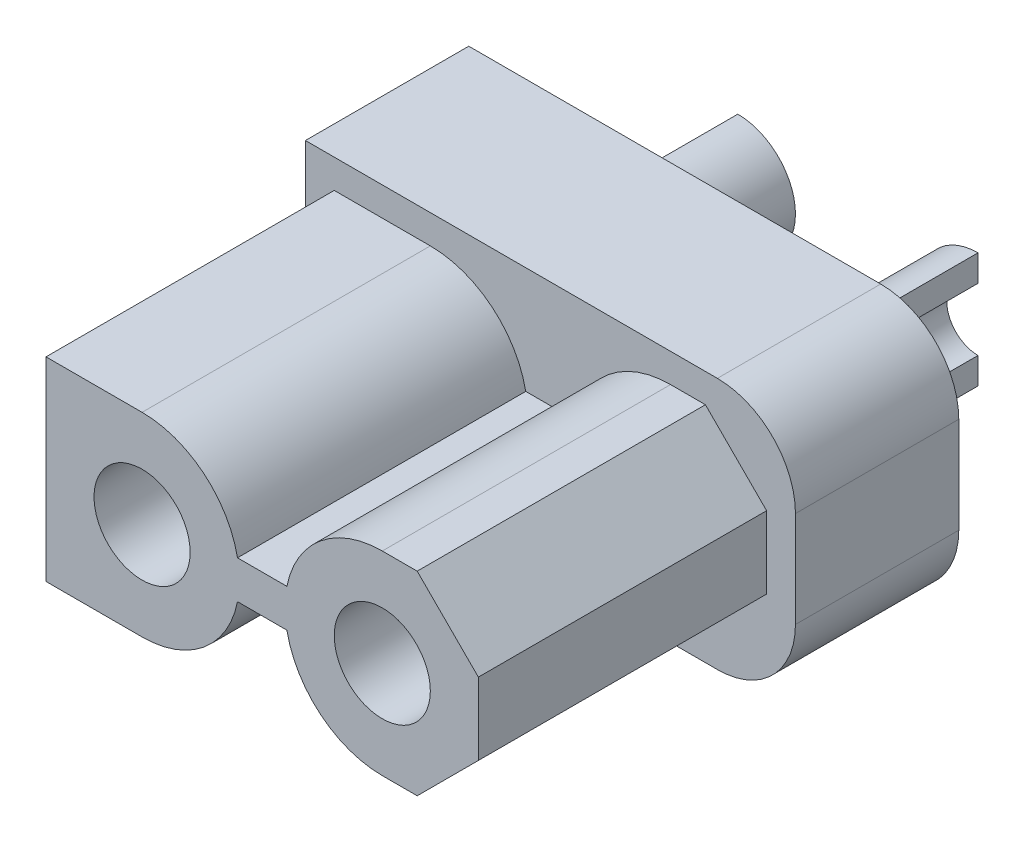
SolidWorks part; units mm, degrees
ref_plane "Front Plane" through (0, 0, 0) normal (0, 0, 1) x (1, 0, 0)
ref_plane "Top Plane" through (0, 0, 0) normal (0, 1, 0) x (1, 0, 0)
ref_plane "Right Plane" through (0, 0, 0) normal (1, 0, 0) x (0, 0, -1)
sketch "Sketch1" plane through (0, 0, 0) normal (0, 0, 1) x (1, 0, 0)
  line L0 (0, 0) -> (10.2, 0) construction
  line L1 (0, -2.625) -> (0, 2.625)
  line L2 (0, 2.625) -> (8.575, 2.625)
  line L4 (10.2, 1) -> (10.2, -1)
  line L5 (5.1, 0) -> (5.1, 1.3562) construction
  line L7 (0, -2.625) -> (8.575, -2.625)
  line L8 (0.5, 2.125) -> (8.3679, 2.125)
  line L9 (8.3679, 2.125) -> (9.7, 0.7929)
  line L10 (9.7, 0.7929) -> (9.7, -0.7929)
  line L11 (8.3679, -2.125) -> (9.7, -0.7929)
  line L12 (0.5, -2.125) -> (8.3679, -2.125)
  line L13 (0.5, -2.125) -> (0.5, 2.125)
  line L14 (8.575, 2.625) -> (10.2, 1) construction
  line L15 (8.575, -2.625) -> (10.2, -1) construction
  circle A0 centre (2.6, 0) radius 1
  circle A2 centre (7.6, 0) radius 1
  arc A3 (8.575, 2.625) -> (10.2, 1) centre (8.575, 1) cw
  arc A4 (8.575, -2.625) -> (10.2, -1) centre (8.575, -1) ccw
  dimension "D6" = 2
  dimension "D1" = 5.25
  dimension "D2" = 10.2
  dimension "D3" = 135
  dimension "D4" = 2.5
  dimension "D7" = 2
  dimension "D5" = 0.5
extrude "Boss-Extrude1" add sketch "Sketch1" along normal blind 3.4 contours L1 L7 A4 L4 A3 L2 L12 L13 L8 L9 L10 L11 | L13 L12 L11 L10 L9 L8 A0 A2 | A2 | A0
ref_plane "Plane1" through (0, 0, 1) normal (0, 0, -1) x (-1, 0, 0)
sketch "Sketch3" plane through (0, 0, 1) normal (0, 0, -1) x (-1, 0, 0)
  line L19 (-5.6139, 0.395) -> (-4.5861, 0.395)
  line L20 (-5.6139, 0.395) -> (-5.6139, -0.395)
  line L21 (-5.6139, -0.395) -> (-4.5861, -0.395)
  line L22 (-4.5861, 0.395) -> (-4.5861, -0.395)
  line L23 (-5.6139, 0.395) -> (-4.5861, -0.395) construction
  line L24 (-8.3265, -2.025) -> (-0.6, -2.025)
  line L25 (-0.6, -2.025) -> (-0.6, 2.025)
  line L26 (-0.6, 2.025) -> (-8.3265, 2.025)
  line L27 (-8.3265, 2.025) -> (-9.6, 0.7515)
  line L28 (-9.6, 0.7515) -> (-9.6, -0.7515)
  line L29 (-9.6, -0.7515) -> (-8.3265, -2.025)
  line L30 (-8.3265, -2.025) -> (-0.6, -2.025)
  line L31 (-0.6, -2.025) -> (-0.6, 2.025)
  line L32 (-0.6, 2.025) -> (-8.3265, 2.025)
  line L33 (-8.3265, 2.025) -> (-9.6, 0.7515)
  line L34 (-9.6, 0.7515) -> (-9.6, -0.7515)
  line L35 (-9.6, -0.7515) -> (-8.3265, -2.025)
  line L36 (-5.6139, -0.395) -> (-4.5861, 0.395) construction
  circle A0 centre (-2.6, 0) radius 2.025
  arc A1 (-7.6, -2.025) -> (-7.6, 2.025) centre (-7.6, 0) ccw
  circle A2 centre (-2.6, 0) radius 1 construction
  circle A3 centre (-7.6, 0) radius 1 construction
  point P3 (-5.1, 0)
  dimension "D2" = 0.79
  dimension "D1" = 0.1
extrude "Boss-Extrude3" add sketch "Sketch3" against normal offset from surface (8.4 mm away) 9.4 contours L20 A1 L32 L33 L34 L35 L30 | L31 A0 L22 | A0 L30 L31 | A0 L31 L32
ref_plane "Plane2" through (0, 0, 11.9) normal (0, 0, 1) x (1, 0, 0)
sketch "Sketch5" plane through (0, 0, 9.4) normal (0, 0, 1) x (1, 0, 0)
  circle A0 centre (7.6, 0) radius 1.2
  circle A1 centre (2.6, 0) radius 1.2
  dimension "D1" = 2.4
extrude "Boss-Extrude6" add sketch "Sketch5" against normal offset from surface (12.4 mm away) 3 up to face at (6.3705, 0, 0) offset beyond the face yes
sketch "Sketch6" plane through (0, 0, -3) normal (0, 0, -1) x (-1, 0, 0)
  circle A0 centre (-2.6, 0) radius 0.65
  circle A1 centre (-7.6, 0) radius 0.65
  circle A3 centre (-2.6, 0) radius 1.2 construction
  circle A4 centre (-7.6, 0) radius 1.2 construction
  dimension "D1" = 0.55
extrude "Cut-Extrude2" cut sketch "Sketch6" against normal up to surface (3 mm away) contours A1 | A0 up to face at (3.8, 0, 0)
sketch "Sketch7" plane through (0, 0, -3) normal (0, 0, -1) x (-1, 0, 0)
  line L0 (-2.6, -1.2) -> (-2.6, 1.2)
  line L1 (-7.6, -1.2) -> (-7.6, 1.2)
  circle A1 centre (-2.6, 0) radius 1.2
  circle A2 centre (-2.6, 0) radius 1.2
  circle A3 centre (-7.6, 0) radius 1.2
  circle A4 centre (-7.6, 0) radius 1.2
  circle M3 centre (-2.6, 0) radius 0.65
  circle M4 centre (-2.6, 0) radius 1.2
  dimension "D1" = 0
  dimension "D2" = 0
extrude "Cut-Extrude3" cut sketch "Sketch7" against normal blind 2.34 contours L0 M4 M3 | L1 A4
sketch "Sketch8" plane through (0, 0, 9.4) normal (0, 0, 1) x (1, 0, 0)
  circle A0 centre (7.6, 0) radius 1
  circle A1 centre (2.6, 0) radius 1
  dimension "D1" = 2
extrude "Cut-Extrude4" cut sketch "Sketch8" against normal up to surface (6 mm away) up to face at (5.5609, 0, 3.4)
